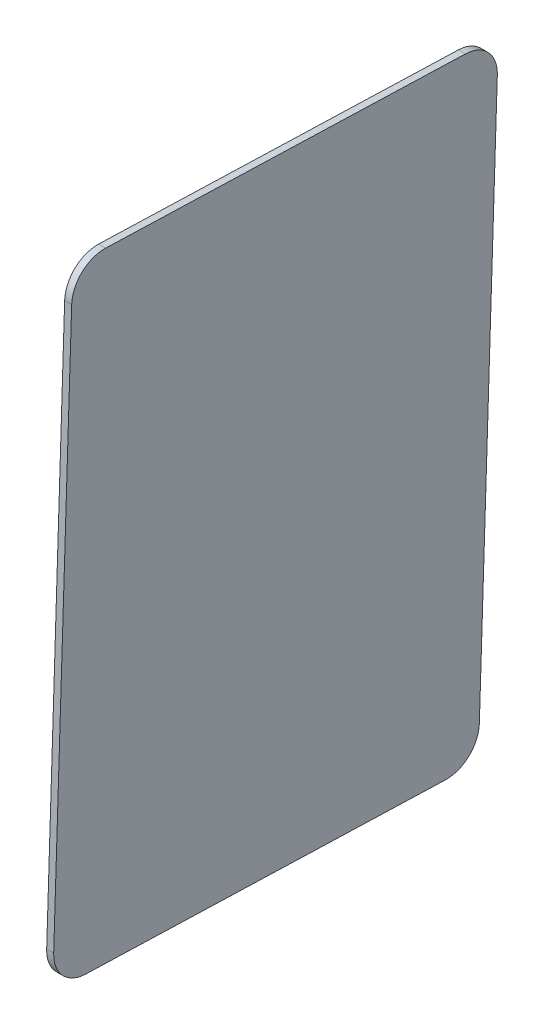
SolidWorks part; units mm, degrees
material "Acrylic (Medium-high impact)"
ref_plane "X-Y Datum" through (0, 0, 0) normal (0, 0, 1) x (1, 0, 0)
ref_plane "X-Z Datum" through (0, 0, 0) normal (0, 1, 0) x (1, 0, 0)
ref_plane "Y-Z Datum" through (0, 0, 0) normal (1, 0, 0) x (0, 0, -1)
sketch "Sketch1" plane through (0, 0, 0) normal (1, 0, 0) x (0, 0, -1)
  line L8 (-8.8585, 93.3982) -> (-4.7923, 218.4271)
  line L9 (-97.9138, 88.8376) -> (-16.5498, 86.1914)
  line L10 (-101.0544, 221.5578) -> (-105.1206, 96.5289)
  line L11 (-11.9991, 226.1184) -> (-93.3631, 228.7646)
  line L12 (-8.8585, 93.3982) -> (-4.7923, 218.4271)
  line L13 (-97.9138, 88.8376) -> (-16.5498, 86.1914)
  line L14 (-101.0544, 221.5578) -> (-105.1206, 96.5289)
  line L15 (-11.9991, 226.1184) -> (-93.3631, 228.7646)
  arc A8 (-16.5498, 86.1914) -> (-8.8585, 93.3982) centre (-16.3076, 93.6405) ccw
  arc A9 (-105.1206, 96.5289) -> (-97.9138, 88.8376) centre (-97.6716, 96.2866) ccw
  arc A10 (-93.3631, 228.7646) -> (-101.0544, 221.5578) centre (-93.6053, 221.3155) ccw
  arc A11 (-4.7923, 218.4271) -> (-11.9991, 226.1184) centre (-12.2413, 218.6694) ccw
  arc A12 (-16.5498, 86.1914) -> (-8.8585, 93.3982) centre (-16.3076, 93.6405) ccw
  arc A13 (-105.1206, 96.5289) -> (-97.9138, 88.8376) centre (-97.6716, 96.2866) ccw
  arc A14 (-93.3631, 228.7646) -> (-101.0544, 221.5578) centre (-93.6053, 221.3155) ccw
  arc A15 (-4.7923, 218.4271) -> (-11.9991, 226.1184) centre (-12.2413, 218.6694) ccw
  dimension "D1" = 0.381
extrude "Boss-Extrude1" add sketch "Sketch1" against normal blind 1.5875
